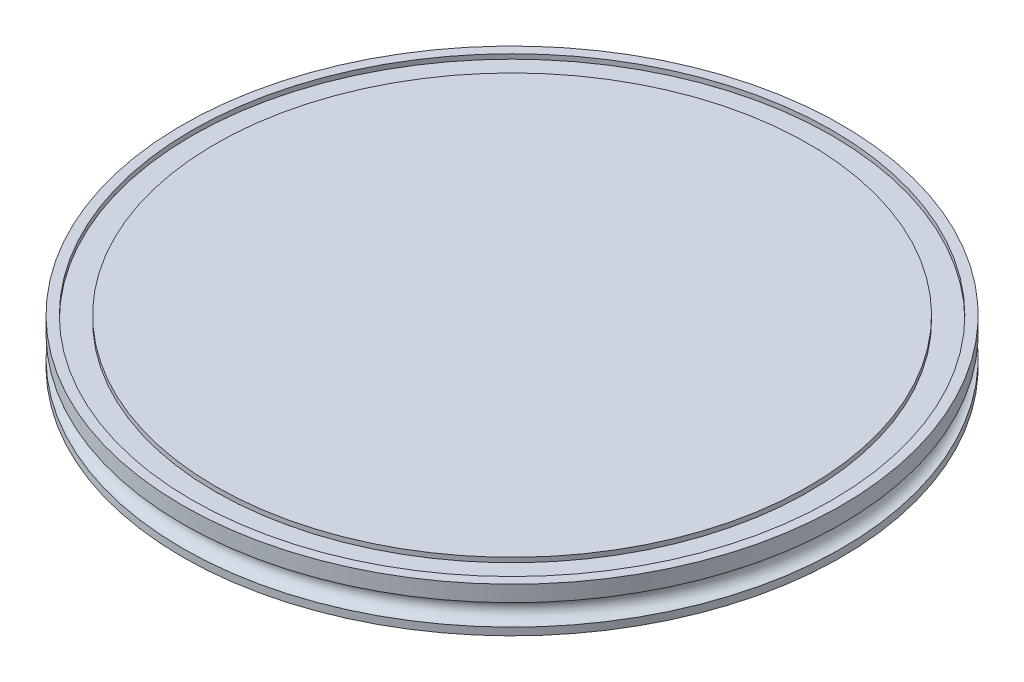
SolidWorks part; units mm, degrees
material "AISI 304"
ref_plane "Front Plane" through (0, 0, 0) normal (0, 0, 1) x (1, 0, 0)
ref_plane "Top Plane" through (0, 0, 0) normal (0, 1, 0) x (1, 0, 0)
ref_plane "Right Plane" through (0, 0, 0) normal (1, 0, 0) x (0, 0, -1)
sketch "Sketch1" plane through (0, 0, 0) normal (0, 0, 1) x (1, 0, 0)
  line L0 (0, 28.207) -> (0, -33.9706) construction
  line L1 (0, 0) -> (0, 12.065)
  line L2 (0, 12.065) -> (80.01, 12.065)
  line L3 (88.9, 12.065) -> (88.9, 7.747)
  line L4 (88.9, 0) -> (76.2, 0)
  line L5 (88.9, 2.032) -> (88.9, 0)
  line L6 (88.9, 12.065) -> (86.36, 12.065)
  line L7 (86.36, 12.065) -> (86.36, 10.795)
  line L8 (86.36, 10.795) -> (80.01, 10.795)
  line L9 (80.01, 10.795) -> (80.01, 12.065)
  line L10 (86.36, 12.065) -> (88.9, 12.065)
  line L11 (76.2, 0) -> (76.2, 2.54)
  line L12 (76.2, 2.54) -> (69.85, 2.54)
  line L13 (69.85, 2.54) -> (69.85, 0)
  line L14 (69.85, 0) -> (0, 0)
  arc A0 (88.9, 7.747) -> (88.9, 2.032) centre (88.9, 4.8895) ccw
  dimension "D3" = 2.8575
  dimension "D1" = 88.9
  dimension "D2" = 12.065
  dimension "D4" = 4.318
  dimension "D6" = 2.54
  dimension "D7" = 6.35
  dimension "D8" = 1.27
  dimension "D9" = 2.54
  dimension "D10" = 76.2
  dimension "D11" = 6.35
revolve "Revolve2" add sketch "Sketch1" angle 360 about L0
sketch "Sketch2" plane through (0, 12.065, 0) normal (0, 1, 0) x (1, 0, 0)
  circle A0 centre (-25.4, -47.752) radius 6.35
  circle A1 centre (25.4, -47.752) radius 6.35
  dimension "D3" = 12.7
  dimension "D4" = 12.7
  dimension "D1" = 25.4
  dimension "D2" = 25.4
  dimension "D5" = 47.752
  dimension "D6" = 47.752
extrude "Cut-Extrude1" cut sketch "Sketch2" against normal through all
sketch "Sketch3" plane through (0, 12.065, 0) normal (0, 1, 0) x (1, 0, 0)
  circle A0 centre (0, 38.1) radius 25.4
  circle A1 centre (25.4, 0) radius 12.7
  circle A2 centre (-25.4, 0) radius 12.7
  circle A3 centre (25.4, -47.752) radius 6.35 construction
  circle A4 centre (-25.4, -47.752) radius 6.35 construction
  point P6 (0, 0)
  dimension "D1" = 50.8
  dimension "D2" = 25.4
  dimension "D3" = 25.4
  dimension "D7" = 47.752
  dimension "D9" = 85.852
  dimension "D4" = 38.1
  dimension "D5" = 25.4
  dimension "D6" = 25.4
  dimension "D8" = 47.752
extrude "Cut-Extrude3" cut sketch "Sketch3" against normal through all
sketch "Sketch4" plane through (0, 12.065, 0) normal (0, 1, 0) x (1, 0, 0)
  circle A2 centre (50.8, -25.4) radius 5.715
  circle A3 centre (50.8, 25.4) radius 5.715
  circle A4 centre (-50.8, -25.4) radius 5.715
  circle A5 centre (-50.8, 25.4) radius 5.715
  circle A6 centre (25.4, 0) radius 12.7 construction
  circle A8 centre (-25.4, 0) radius 12.7 construction
  dimension "D1" = 11.43
  dimension "D2" = 11.43
  dimension "D3" = 11.43
  dimension "D4" = 11.43
  dimension "D5" = 25.4
  dimension "D6" = 25.4
  dimension "D7" = 25.4
  dimension "D8" = 25.4
  dimension "D9" = 25.4
  dimension "D10" = 25.4
  dimension "D11" = 25.4
  dimension "D12" = 25.4
extrude "Cut-Extrude4" cut sketch "Sketch4" against normal through all
sketch "Sketch5" plane through (0, 12.065, 0) normal (0, 1, 0) x (1, 0, 0)
  circle A0 centre (-25.4, -47.752) radius 6.35
  circle A1 centre (-50.8, -25.4) radius 5.715
  circle A2 centre (-25.4, 0) radius 12.7
  circle A3 centre (0, 38.1) radius 25.4
  circle A4 centre (-50.8, 25.4) radius 5.715
  circle A5 centre (50.8, 25.4) radius 5.715
  circle A6 centre (25.4, 0) radius 12.7
  circle A7 centre (25.4, -47.752) radius 6.35
  circle A8 centre (50.8, -25.4) radius 5.715
extrude "Boss-Extrude1" add sketch "Sketch5" against normal through all
